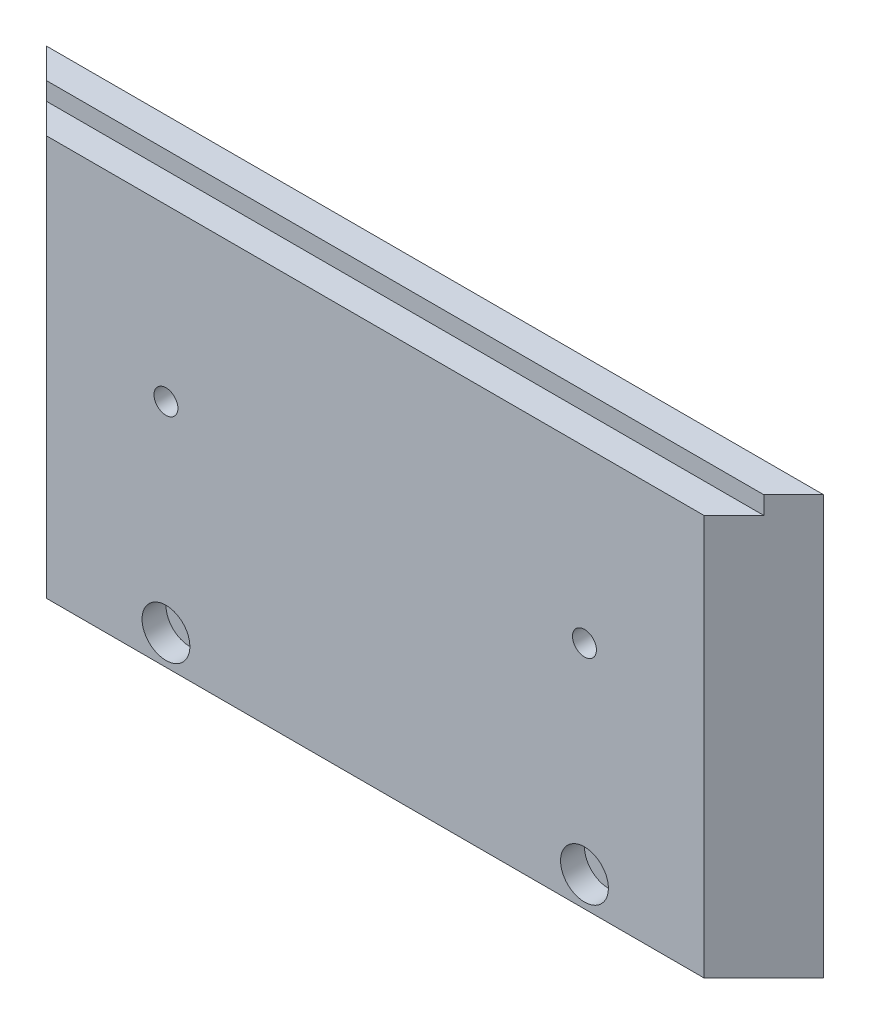
SolidWorks part; units mm, degrees
ref_plane "Front Plane" through (0, 0, 0) normal (0, 0, 1) x (1, 0, 0)
ref_plane "Top Plane" through (0, 0, 0) normal (0, 1, 0) x (1, 0, 0)
ref_plane "Right Plane" through (0, 0, 0) normal (1, 0, 0) x (0, 0, -1)
sketch "Sketch1" plane through (0, 0, 0) normal (0, 1, 0) x (1, 0, 0)
  line L0 (0, 10) -> (10, 0)
  line L1 (0, 0) -> (130, 0)
  line L2 (0, 0) -> (0, 10)
  line L3 (0, 10) -> (130, 10)
  line L4 (130, 0) -> (130, 10)
  line L5 (130, 10) -> (120, 0)
  dimension "D1" = 10
  dimension "D2" = 130
  dimension "D3" = 10
  dimension "D4" = 10
extrude "Boss-Extrude1" add sketch "Sketch1" along normal blind 70 contours L5 L3 L0 L1
sketch "Sketch2" plane through (0, 70, 0) normal (0, 1, 0) x (1, 0, 0)
  line L0 (5, 5) -> (125, 5)
  line L1 (0, 10) -> (10, 0) construction
  line L2 (130, 10) -> (120, 0) construction
  line M2 (120, 0) -> (130, 10)
  line M4 (0, 10) -> (10, 0)
  line M5 (10, 0) -> (120, 0)
extrude "Cut-Extrude1" cut sketch "Sketch2" against normal blind 3 and the other way through all contours L0 M4 M5 M2
sketch "Sketch3" plane through (0, 0, 0) normal (0, 0, 1) x (1, 0, 0)
  line L7 (10, 67) -> (10, 0) construction
  line L8 (120, 67) -> (120, 0) construction
  line L9 (10, 0) -> (120, 0) construction
  circle A0 centre (30, 5) radius 4
  circle A1 centre (100, 5) radius 4
  dimension "D1" = 8
  dimension "D2" = 8
  dimension "D3" = 20
  dimension "D4" = 20
  dimension "D5" = 5
  dimension "D6" = 5
extrude "Cut-Extrude2" cut sketch "Sketch3" against normal blind 4
sketch "Sketch4" plane through (0, 0, 0) normal (0, 0, 1) x (1, 0, 0)
  line L0 (10, 67) -> (120, 67) construction
  line L1 (120, 67) -> (120, 0) construction
  line L2 (10, 67) -> (10, 0) construction
  circle A0 centre (30, 38.5) radius 2
  circle A1 centre (100, 38.5) radius 2
  dimension "D1" = 4
  dimension "D2" = 4
  dimension "D3" = 28.5
  dimension "D4" = 28.5
  dimension "D5" = 20
  dimension "D6" = 20
extrude "Cut-Extrude3" cut sketch "Sketch4" against normal blind 4 contours A0 | A1
